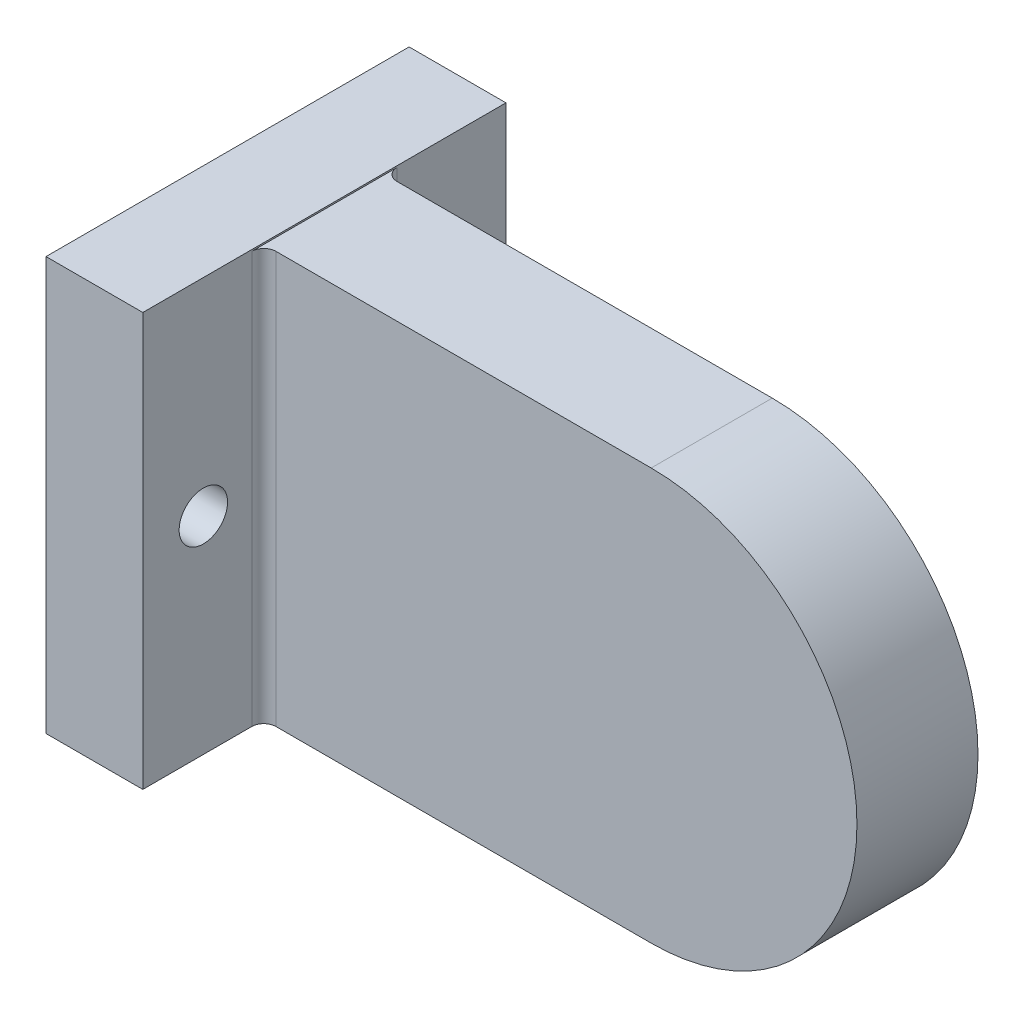
SolidWorks part; units mm, degrees
ref_plane "Front Plane" through (0, 0, 0) normal (0, 0, 1) x (1, 0, 0)
ref_plane "Top Plane" through (0, 0, 0) normal (0, 1, 0) x (1, 0, 0)
ref_plane "Right Plane" through (0, 0, 0) normal (1, 0, 0) x (0, 0, -1)
sketch "Sketch2" plane through (0, 0, 0) normal (0, 0, 1) x (1, 0, 0)
  line L4 (22.9129, 16.376) -> (22.9129, -18.1515) construction
  line L5 (22.9129, 16.1123) -> (-17.0871, 16.1123)
  line L6 (22.9129, -17.8877) -> (-17.0871, -17.8877)
  line L7 (-17.0871, 16.1123) -> (-17.0871, -17.8877)
  arc A2 (22.9129, -17.8877) -> (22.9129, 16.1123) centre (22.9129, -0.8877) ccw
  dimension "D4" = 40
  dimension "D1" = 34
  dimension "D2" = 40
extrude "Boss-Extrude1" add sketch "Sketch2" along normal blind 10
sketch "Sketch3" plane through (-17.0871, 0, 0) normal (-1, 0, 0) x (0, 0, 1)
  line L0 (10, -17.8877) -> (0, -17.8877) construction
  line L1 (-10, 16.2392) -> (20, 16.2392)
  line L2 (-10, 16.2392) -> (-10, -17.8877)
  line L3 (-10, -17.8877) -> (20, -17.8877)
  line L4 (20, 16.2392) -> (20, -17.8877)
  point P4 (5, -17.8877)
  point P7 (5, -17.8877)
  dimension "D1" = 30
extrude "Boss-Extrude2" add sketch "Sketch3" against normal blind 8
fillet "Fillet1" radius 1 2 edges at (-9.0871, -0.8877, 0) (-9.0871, -0.8877, 10)
sketch "Sketch5" plane through (-17.0871, 0, 0) normal (-1, 0, 0) x (0, 0, 1)
  line L0 (5, 16.2392) -> (5, -17.8877) construction
  line L1 (20, 16.2392) -> (-10, 16.2392) construction
  line L2 (20, -17.8877) -> (-10, -17.8877) construction
  line L3 (-10, -0.8243) -> (20, -0.8243) construction
  line L4 (-10, 16.2392) -> (-10, -17.8877) construction
  line L5 (20, -17.8877) -> (20, 16.2392) construction
  circle A0 centre (-5, -0.8243) radius 2
  circle A1 centre (15, -0.8243) radius 2
  dimension "D1" = 4
  dimension "D2" = 4
  dimension "D3" = 5
  dimension "D4" = 5
extrude "Cut-Extrude2" cut sketch "Sketch5" against normal through all contours A1 | A0
sketch "Sketch6" plane through (0, 0, 0) normal (0, 0, -1) x (-1, 0, 0)
  line L0 (-39.9129, -0.8877) -> (8.0871, -0.8877) construction
  line L1 (8.0871, -17.8877) -> (8.0871, 16.1123) construction
  line L3 (17.0871, 16.2392) -> (17.0871, -17.8877) construction
  arc A0 (-22.9129, 16.1123) -> (-22.9129, -17.8877) centre (-22.9129, -0.8877) ccw construction
  circle A1 centre (-22.9129, -0.8877) radius 13.65
  point P9 (0, 0)
  dimension "D1" = 27.3
  dimension "D2" = 40
extrude "Cut-Extrude3" cut sketch "Sketch6" against normal blind 8
